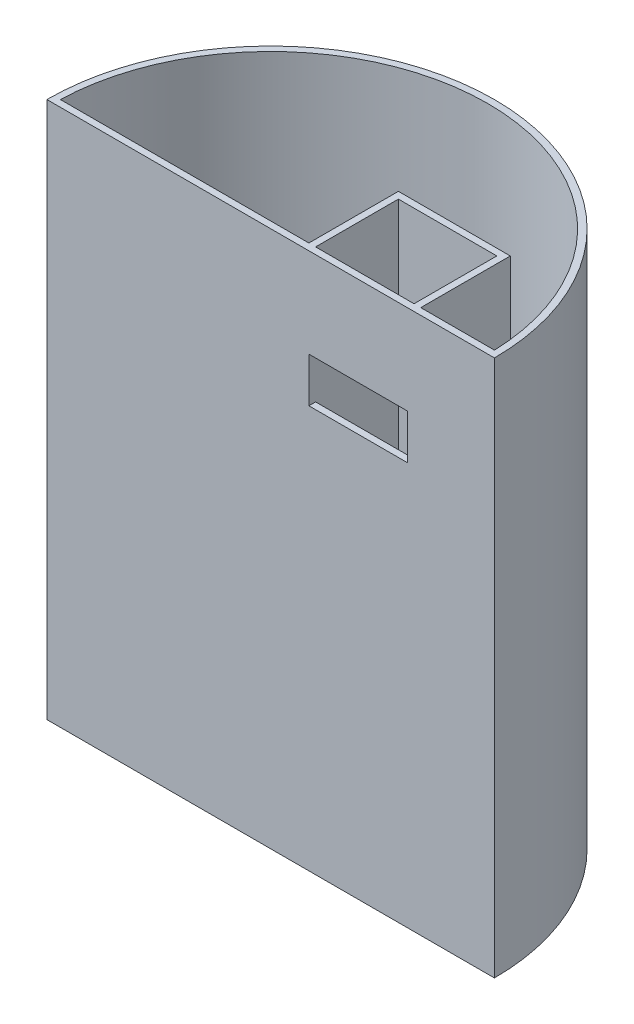
SolidWorks part; units mm, degrees
material "POM 乙缩醛共聚物"
ref_plane "前视基准面" through (0, 0, 0) normal (0, 0, 1) x (1, 0, 0)
ref_plane "上视基准面" through (0, 0, 0) normal (0, 1, 0) x (1, 0, 0)
ref_plane "右视基准面" through (0, 0, 0) normal (1, 0, 0) x (0, 0, -1)
sketch "草图2" plane through (0, 0, 0) normal (0, 1, 0) x (1, 0, 0)
  line L0 (0, 0) -> (200, 0)
  arc A0 (0, 0) -> (200, 0) centre (100, 0) cw
  dimension "D1" = 200
extrude "凸台-拉伸1" add sketch "草图2" along normal blind 240
ref_plane "基准面4" through (0, 4, 0) normal (0, 1, 0) x (1, 0, 0)
sketch "草图4" plane through (0, 4, 0) normal (0, 1, 0) x (1, 0, 0)
  line L0 (0, 0) -> (200, 0) construction
  line L1 (3, 3) -> (197, 3)
  arc A0 (200, 0) -> (0, 0) centre (100, 0) ccw construction
  arc A1 (3, 3) -> (197, 3) centre (100, -0.0687) cw
  point P0 (100, 97)
  point P4 (100, 3)
  point P7 (3, 3)
  point P8 (197, 3)
  dimension "D3" = 97
  dimension "D1" = 97
  dimension "D2" = 3
  dimension "D4" = 97
extrude "切除-拉伸3" cut sketch "草图4" along direction (0, -1, 0) on the side against the normal through all and the other way through all from surface at 0 starting at plane "基准面4"
sketch "草图10" plane through (0, 0, 0) normal (0, 1, 0) x (1, 0, 0)
  line L1 (3, 3) -> (197, 3)
  line L2 (3, 3) -> (197, 3)
  arc A0 (3, 3) -> (197, 3) centre (100, -0.0687) cw
  arc A2 (197, 3) -> (3, 3) centre (100, -0.0687) ccw
  dimension "D1" = 0
extrude "凸台-拉伸3" add sketch "草图10" along normal blind 3
ref_plane "基准面5" through (0, 0, -3) normal (0, 0, -1) x (-1, 0, 0)
sketch "草图11" plane through (0, 0, -3) normal (0, 0, -1) x (-1, 0, 0)
  line L0 (-164.0823, 240) -> (-164.0823, 54)
  line L1 (0, 240) -> (-200, 240) construction
  line L2 (55, 4) -> (-55, 4) construction
  line L3 (-164.0823, 54) -> (-114.0823, 54)
  line L4 (-114.0823, 54) -> (-114.0823, 240)
  line L6 (-164.0823, 240) -> (-114.0823, 240)
  dimension "D1" = 50
  dimension "D2" = 50
extrude "凸台-拉伸5" add sketch "草图11" along normal blind 40
ref_plane "基准面6" through (0, 240, 0) normal (0, 1, 0) x (1, 0, 0)
sketch "草图12" plane through (0, 240, 0) normal (0, 1, 0) x (1, 0, 0)
  line L0 (106.7, 3) -> (-106.7, 3) construction
  line L1 (114.0823, 43) -> (114.0823, 3) construction
  line L2 (114.0823, 43) -> (164.0823, 43) construction
  line L3 (164.0823, 43) -> (164.0823, 3) construction
  line L4 (117.0823, 3) -> (117.0823, 40)
  line L5 (117.0823, 40) -> (128.0823, 40)
  line L6 (161.0823, 40) -> (161.0823, 3)
  line L7 (161.0823, 3) -> (131.0823, 3)
  line L12 (131.0823, 40) -> (161.0823, 40)
  line L13 (128.0823, 3) -> (117.0823, 3)
  line L14 (128.0823, 40) -> (131.0823, 40)
  line L15 (128.0823, 3) -> (131.0823, 3)
  point P0 (117.0823, 3)
  point P5 (117.0823, 40)
  point P8 (161.0823, 40)
  point P13 (131.0823, 40)
  point P16 (128.0823, 40)
  dimension "D1" = 3
  dimension "D2" = 3
  dimension "D3" = 3
  dimension "D4" = 30
  dimension "D5" = 3
extrude "切除-拉伸4" cut sketch "草图12" against normal blind 183
sketch "草图13" plane through (0, 240, 0) normal (0, 1, 0) x (1, 0, 0)
  circle A0 centre (144.3314, 21.2134) radius 10
  circle A1 centre (123.8353, 21.2134) radius 3
  circle A2 centre (123.8353, 10.3231) radius 5.2
  circle A3 centre (123.8353, 33.1654) radius 5.2
  dimension "D1" = 10.4
extrude "切除-拉伸5" cut sketch "草图13" against normal blind 187
sketch "草图15" plane through (0, 240, 0) normal (0, 1, 0) x (1, 0, 0)
  line L0 (0, 0) -> (200, 0) construction
  point P0 (117.0823, 0)
  point P1 (128.0823, 0)
  point P4 (131.0823, 0)
  point P5 (161.0823, 0)
sketch "草图16" plane through (0, 0, 0) normal (0, 0, 1) x (1, 0, 0)
  line L0 (117.0823, 200) -> (161.0823, 200)
  line L1 (161.0823, 200) -> (161.0823, 180)
  line L2 (161.0823, 180) -> (117.0823, 180)
  line L3 (117.0823, 180) -> (117.0823, 200)
  point P0 (117.0823, 200)
  point P1 (117.0823, 180)
  dimension "D1" = 40
  dimension "D2" = 20
extrude "切除-拉伸6" cut sketch "草图16" against normal blind 3
